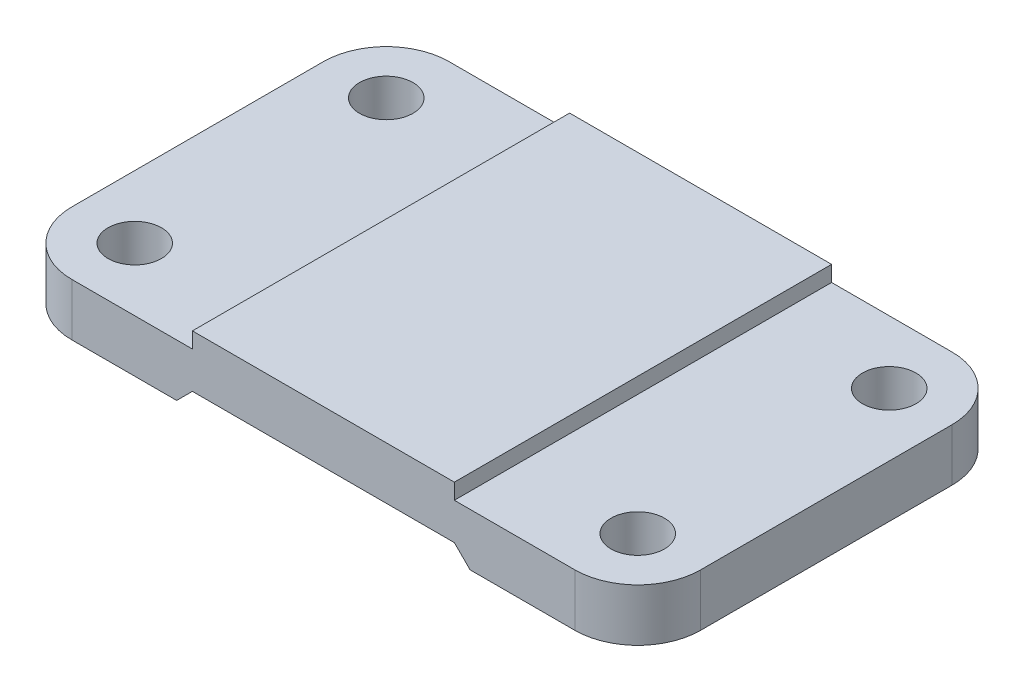
SolidWorks part; units mm, degrees
ref_plane "Front Plane" through (0, 0, 0) normal (0, 0, 1) x (1, 0, 0)
ref_plane "Top Plane" through (0, 0, 0) normal (0, 1, 0) x (1, 0, 0)
ref_plane "Right Plane" through (0, 0, 0) normal (1, 0, 0) x (0, 0, -1)
sketch "Sketch1" plane through (0, 0, 0) normal (0, 1, 0) x (1, 0, 0)
  line L0 (-48, 36) -> (48, 36)
  line L1 (60, 24) -> (60, -24)
  line L2 (48, -36) -> (-48, -36)
  line L3 (-60, -24) -> (-60, 24)
  line L4 (0, 65) -> (0, -84.1176) construction
  arc A0 (-60, -24) -> (-48, -36) centre (-48, -24) ccw
  arc A1 (48, -36) -> (60, -24) centre (48, -24) ccw
  arc A2 (60, 24) -> (48, 36) centre (48, 24) ccw
  arc A3 (-60, 24) -> (-48, 36) centre (-48, 24) cw
  circle A4 centre (-48, 24) radius 5.1
  circle A5 centre (-48, -24) radius 5.1
  circle A6 centre (48, -24) radius 5.1
  circle A7 centre (48, 24) radius 5.1
  point P3 (0, 36)
  point P7 (-60, -36)
  point P12 (60, 36)
  point P15 (-60, 36)
  dimension "D3" = 12
  dimension "D4" = 10.2
  dimension "D5" = 10.2
  dimension "D1" = 120
  dimension "D2" = 72
  dimension "D6" = 36
extrude "Boss-Extrude1" add sketch "Sketch1" along normal blind 13 contours L3 A3 L0 A2 L1 A1 L2 A0 | A5 | A4 | A7 | A6
sketch "Sketch2" plane through (0, 0, 0) normal (0, 0, 1) x (1, 0, 0)
  line L1 (25, 13) -> (-25, 13)
  line L2 (48, 13) -> (-48, 13) construction
  line L3 (25, 13) -> (25, 10)
  line L4 (25, 10) -> (60, 10)
  line L5 (60, 13) -> (60, 0) construction
  line L6 (-25, 13) -> (-25, 10)
  line L7 (-25, 10) -> (-60, 10)
  line L8 (-60, 13) -> (-60, 0) construction
  line L9 (-25, 13) -> (-60, 13)
  line L10 (-60, 13) -> (-60, 10)
  line L11 (25, 13) -> (60, 13)
  line L12 (60, 13) -> (60, 10)
  point P0 (0, 13)
  dimension "D1" = 50
  dimension "D2" = 3
  dimension "D3" = 3
extrude "Cut-Extrude1" cut sketch "Sketch2" against normal through all both and the other way through all contours L6 L7 L10 L9 | L3 L4 L12 L11
sketch "Sketch3" plane through (0, 0, 0) normal (0, 0, 1) x (1, 0, 0)
  line L0 (0, -11.9246) -> (0, 39.4457)
  line L1 (-28, 0) -> (28, 0)
  line L2 (48, 0) -> (-48, 0) construction
  line L3 (-60, 0) -> (-60, 3)
  line L4 (-60, 10) -> (-60, 0) construction
  line L5 (-60, 3) -> (59.8018, 3)
  line L6 (59.8018, 3) -> (60, 0)
  line L7 (-28, 0) -> (-25, 3)
  line L8 (28, 0) -> (25, 3)
  line L9 (-28, 0) -> (0, 0)
  line L10 (0, 0) -> (27.0167, 0)
  point P8 (0, 0)
  dimension "D1" = 56
  dimension "D2" = 3
  dimension "D3" = 45
extrude "Cut-Extrude2" cut sketch "Sketch3" against normal through all both and the other way through all contours L7 L1 L0 L5 | L1 L8 L5 L0
